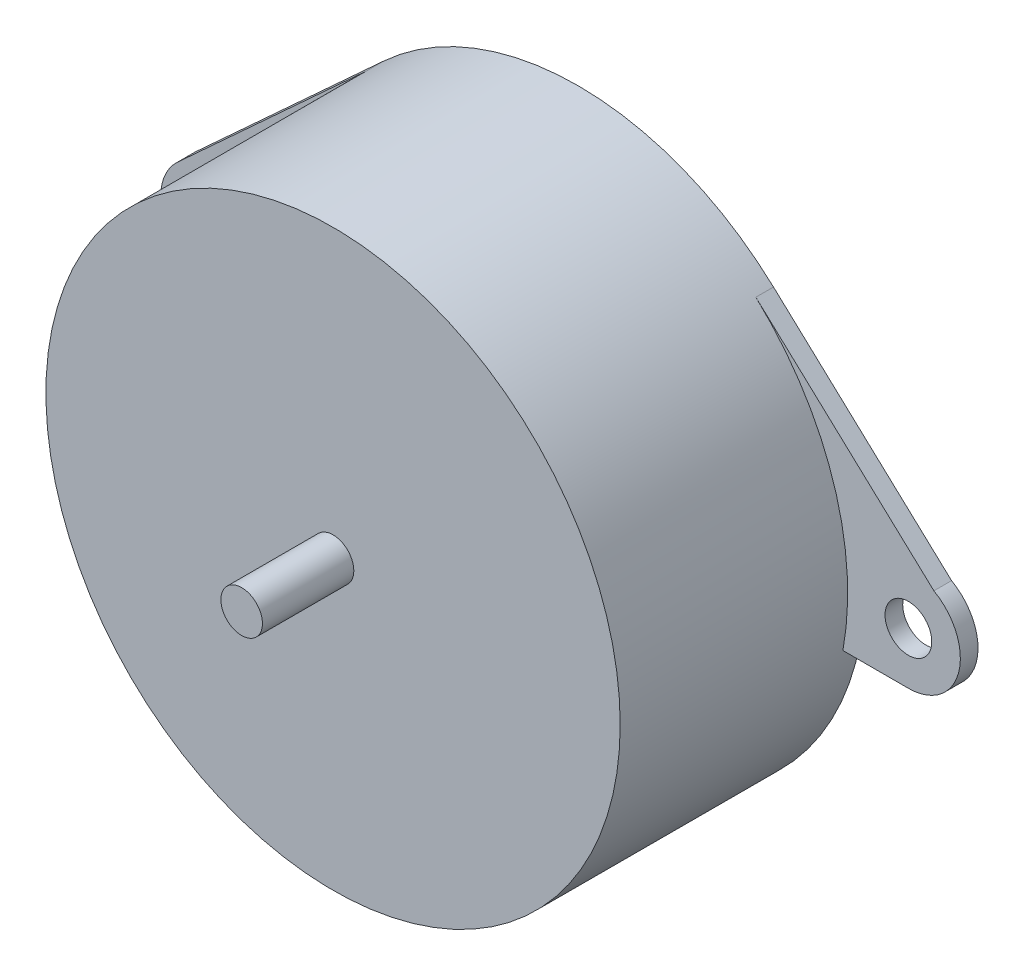
SolidWorks part; units mm, degrees
ref_plane "Alzado" through (0, 0, 0) normal (0, 0, 1) x (1, 0, 0)
ref_plane "Planta" through (0, 0, 0) normal (0, 1, 0) x (1, 0, 0)
ref_plane "Vista lateral" through (0, 0, 0) normal (1, 0, 0) x (0, 0, -1)
sketch "Croquis1" plane through (0, 0, 0) normal (0, 0, 1) x (1, 0, 0)
  circle A0 centre (0, 0) radius 27.65
  dimension "D1" = 55.3
extrude "Saliente-Extruir1" add sketch "Croquis1" along normal blind 21.9
sketch "Croquis2" plane through (0, 0, 21.9) normal (0, 0, 1) x (1, 0, 0)
  circle A1 centre (0, 0) radius 2
  dimension "D1" = 4
extrude "Saliente-Extruir2" add sketch "Croquis2" along normal blind 8.8 and the other way blind 34
sketch "Croquis3" plane through (0, 0, 0) normal (0, 0, -1) x (-1, 0, 0)
  line L0 (36.8806, 3.684) -> (18.6947, 20.3723)
  line L1 (-35.9552, 4.3557) -> (-18.8079, 20.2678)
  line L2 (-33.5, -5) -> (-27.1942, -5)
  line L3 (33.5, -5) -> (27.1942, -5)
  circle A0 centre (0, 0) radius 27.65 construction
  circle A1 centre (0, 0) radius 27.65
  circle A2 centre (33.5, 0) radius 5
  circle A3 centre (-33.5, 0) radius 5
  circle A4 centre (33.5, 0) radius 2.25
  circle A5 centre (-33.5, 0) radius 2.25
  circle M1 centre (0, 0) radius 27.65
  dimension "D1" = 10
  dimension "D2" = 10
  dimension "D3" = 4.5
  dimension "D4" = 4.5
  dimension "D5" = 33.5
  dimension "D6" = 33.5
extrude "Saliente-Extruir3" add sketch "Croquis3" along normal blind 1.7 contours M1 | A3 L2 L1 M1 | L1 A3 A5 | A2 L0 L3 M1 | A2 A4
sketch "Croquis4" plane through (0, 0, -1.7) normal (0, 0, -1) x (-1, 0, 0)
  circle A0 centre (0, 0) radius 5.55
  dimension "D1" = 11.1
extrude "Saliente-Extruir4" add sketch "Croquis4" along normal blind 2
